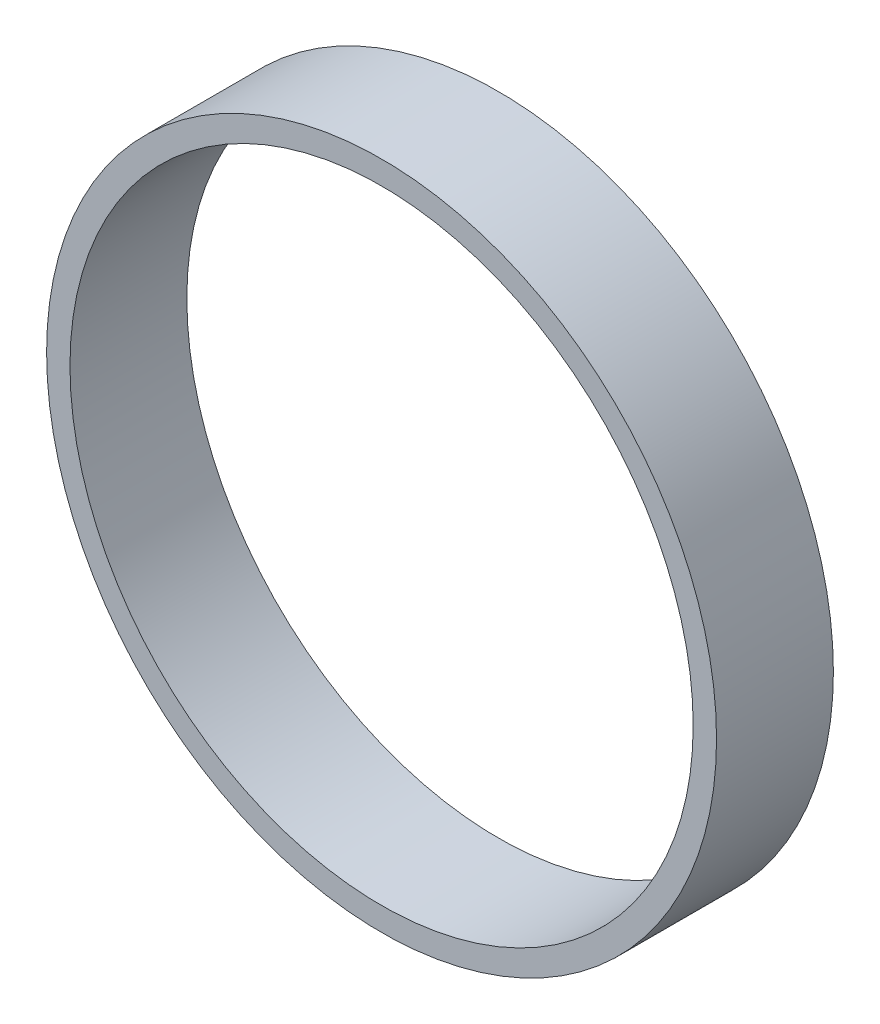
SolidWorks part; units mm, degrees
ref_plane "Front Plane" through (0, 0, 0) normal (0, 0, 1) x (1, 0, 0)
ref_plane "Top Plane" through (0, 0, 0) normal (0, 1, 0) x (1, 0, 0)
ref_plane "Right Plane" through (0, 0, 0) normal (1, 0, 0) x (0, 0, -1)
sketch "Sketch1" plane through (0, 0, 0) normal (0, 0, 1) x (1, 0, 0)
  circle A0 centre (0, 0) radius 54.61
  circle A1 centre (0, 0) radius 50.8
  dimension "D1" = 3.81
  dimension "D2" = 101.6
extrude "Boss-Extrude1" add sketch "Sketch1" along normal blind 19.05
